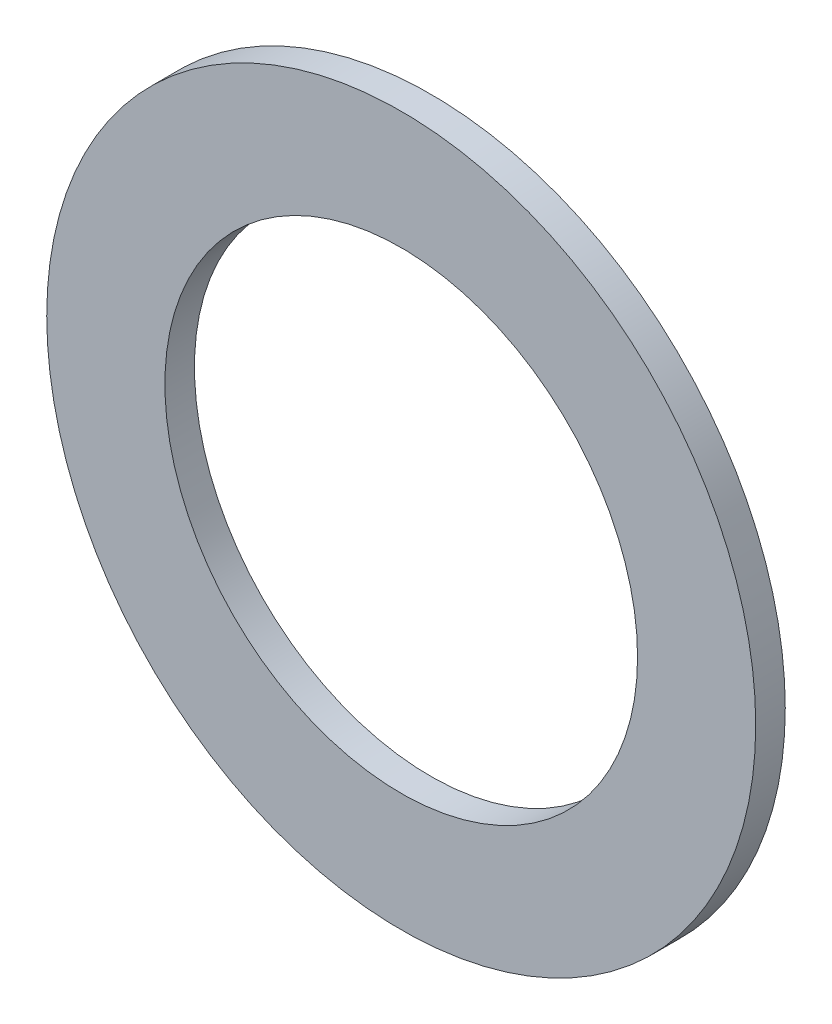
SolidWorks part; units mm, degrees
ref_plane "Front Plane" through (0, 0, 0) normal (0, 0, 1) x (1, 0, 0)
ref_plane "Top Plane" through (0, 0, 0) normal (0, 1, 0) x (1, 0, 0)
ref_plane "Right Plane" through (0, 0, 0) normal (1, 0, 0) x (0, 0, -1)
sketch "Sketch1" plane through (0, 0, 0) normal (0, 0, 1) x (1, 0, 0)
  circle A0 centre (0, 0) radius 12
  dimension "D1" = 24
extrude "Boss-Extrude1" add sketch "Sketch1" along normal blind 1
sketch "Sketch2" plane through (0, 0, 1) normal (0, 0, 1) x (1, 0, 0)
  circle A0 centre (0, 0) radius 8
  dimension "D1" = 16
extrude "Cut-Extrude1" cut sketch "Sketch2" against normal blind 1
